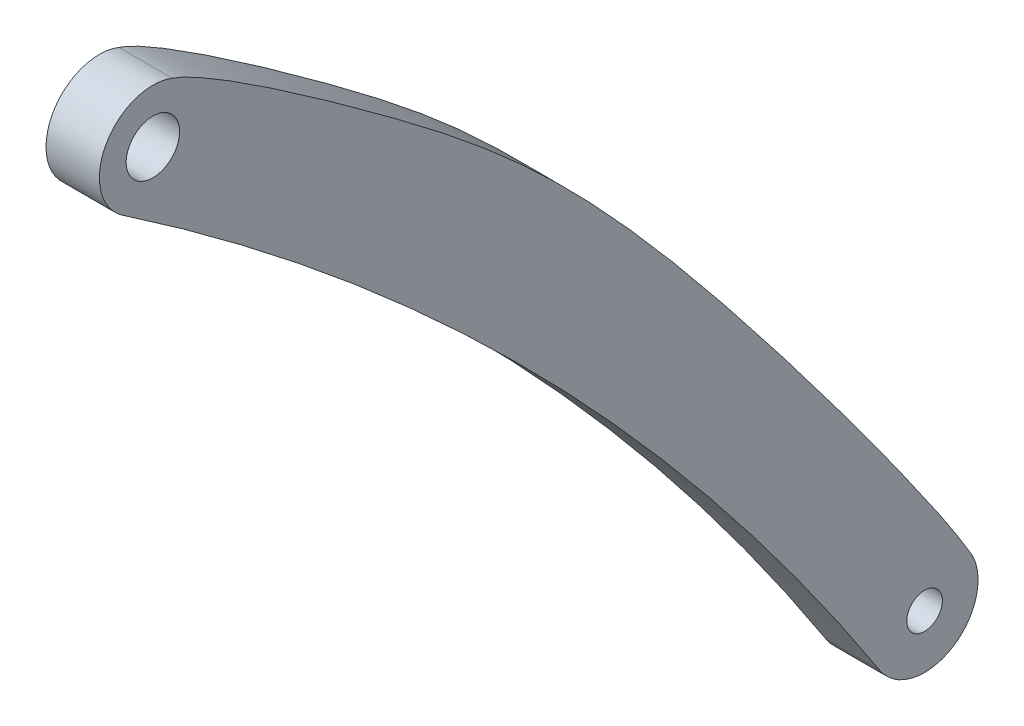
SolidWorks part; units mm, degrees
ref_plane "Front Plane" through (0, 0, 0) normal (1, 0, 0) x (0, 1, 0)
ref_plane "Top Plane" through (0, 0, 0) normal (0, 0, 1) x (0, 1, 0)
ref_plane "Right Plane" through (0, 0, 0) normal (0, 1, 0) x (-1, 0, 0)
sketch "Sketch1" plane through (0, 0, 0) normal (1, 0, 0) x (0, 1, 0)
  line L0 (34.9544, 81.6423) -> (174.7722, 81.6423) construction
  line L1 (65.8943, 10.0491) -> (83.7948, 55.6624) construction
  line L2 (83.7948, 55.6624) -> (52.1805, 74.3019) construction
  line L3 (52.1805, 74.3019) -> (65.8943, 10.0491) construction
  line L4 (83.7948, 55.6624) -> (128.0091, 98.9834) construction
  line L5 (128.0091, 98.9834) -> (90.89, 132.4822) construction
  line L6 (90.89, 132.4822) -> (75.2816, 94.0293) construction
  line L7 (75.2816, 94.0293) -> (83.7948, 55.6624) construction
  line L8 (52.1805, 74.3019) -> (39.1862, 111.4975) construction
  line L9 (39.1862, 111.4975) -> (90.89, 132.4822) construction
  line L10 (39.1862, 111.4975) -> (75.2816, 94.0293) construction
  line L11 (128.0091, 98.9834) -> (113.2816, 101.8293) construction
  dimension "D1" = 49
  dimension "D2" = 65.7
  dimension "D3" = 36.7
  dimension "D4" = 61.9
  dimension "D5" = 50
  dimension "D6" = 41.5
  dimension "D7" = 39.3
  dimension "D8" = 55.8
  dimension "D9" = 39.4
  dimension "D10" = 40.1
  dimension "D11" = 15
  dimension "D12" = 7.8
  dimension "D13" = 38
sketch "Sketch3" plane through (0, 0, 0) normal (1, 0, 0) x (0, 1, 0)
  circle A0 centre (52.1805, 74.3019) radius 10
  arc A2 (85.2864, 65.5506) -> (93.4171, 52.9402) centre (83.7948, 55.6624) ccw
  arc A3 (130.5344, 89.3075) -> (118.0926, 97.6938) centre (128.0091, 98.9834) ccw
  circle A5 centre (75.2816, 94.0293) radius 10
  circle A6 centre (39.1862, 111.4975) radius 10
  arc A7 (100.1088, 136.3569) -> (93.5623, 122.8459) centre (90.89, 132.4822) ccw
  circle A14 centre (39.1862, 111.4975) radius 1
  circle A21 centre (90.89, 132.4822) radius 1
  circle A22 centre (128.0091, 98.9834) radius 1.5
  arc A24 (93.4171, 52.9402) -> (130.5344, 89.3075) centre (11.9212, 173.2419) ccw
  arc A25 (85.2864, 65.5506) -> (118.0926, 97.6938) centre (11.9212, 173.2419) ccw
  circle A27 centre (83.7948, 55.6624) radius 1
  dimension "D1" = 20
  dimension "D2" = 2
  dimension "D3" = 2
  dimension "D4" = 2
  dimension "D5" = 3
extrude "Boss-Extrude3" add sketch "Sketch3" along normal blind 3 contours A25 A2 A24 A3 A27 A22
scale "Scale1" scale about centroid uniform scaling yes scale factor 2
sketch "Sketch4" plane through (4.5, 0, 0) normal (1, 0, 0) x (0, 1, 0)
  arc A0 (57.3746, 40.2492) -> (63.696, 30.0518) centre (60.6344, 35.2119) ccw
  arc A1 (154.6422, 119.6461) -> (144.0935, 125.2157) centre (149.0631, 121.8538) ccw
  arc A3 (57.3746, 40.2492) -> (144.0935, 125.2157) centre (-107.9547, 295.725) ccw
  arc A12 (60.8208, 65.2114) -> (119.0661, 122.2798) centre (-83.1128, 270.3708) ccw
  arc A13 (60.8208, 65.2114) -> (88.1837, 23.3361) centre (60.6344, 35.2119) ccw
  arc A14 (88.1837, 23.3361) -> (160.3742, 94.0678) centre (-83.1128, 270.3708) ccw
  arc A15 (160.3742, 94.0678) -> (119.0661, 122.2798) centre (149.0631, 121.8538) ccw
  arc A16 (60.8208, 65.2114) -> (119.0661, 122.2798) centre (-83.1128, 270.3708) ccw
  arc A17 (60.8208, 65.2114) -> (88.1837, 23.3361) centre (60.6344, 35.2119) ccw
  arc A18 (88.1837, 23.3361) -> (160.3742, 94.0678) centre (-83.1128, 270.3708) ccw
  arc A19 (160.3742, 94.0678) -> (119.0661, 122.2798) centre (149.0631, 121.8538) ccw
  spline S0 degree 3 poles (63.696, 30.0518) (71.2688, 34.5449) (116.1697, 67.6728) (134.0372, 87.7638) (153.6345, 116.2831) (154.6819, 119.7736) (154.7683, 119.9963) knots 0 0 0 0 0.217779 0.657591 0.944552 0.949785 0.949785 0.949785 0.949785
  point P4 (85.3581, 42.0885)
  point P7 (89.1125, 42.7172)
  point P13 (134.5319, 87.9833)
  point P14 (134.8428, 86.542)
  point P16 (91.9707, 47.719)
  point P18 (133.1755, 88.2093)
  point P19 (97.4488, 54.388)
  point P20 (134.3664, 90.8293)
  point P21 (153.6118, 117.9411)
  point P22 (154.6422, 119.6461)
  point P23 (139.0194, 95.7233)
  arc M9 (129.2301, 119.2747) -> (63.6178, 54.9882) centre (-83.1128, 270.3708) cw
  arc M10 (63.6178, 54.9882) -> (79.8791, 29.7674) centre (60.6344, 35.2119) ccw
  arc M11 (79.8791, 29.7674) -> (154.1138, 102.502) centre (-83.1128, 270.3708) ccw
  arc M12 (154.1138, 102.502) -> (129.2301, 119.2747) centre (149.0631, 121.8538) ccw
  dimension "D1" = 12
  dimension "D2" = 12
  dimension "D3" = 10
extrude "Cut-Extrude1" cut sketch "Sketch4" against normal through all both and the other way through all contours S0 A0 A3 A1 M12 M9 M10 M11 | A18 A19 A16 A17 M9 M12 M11 M10
